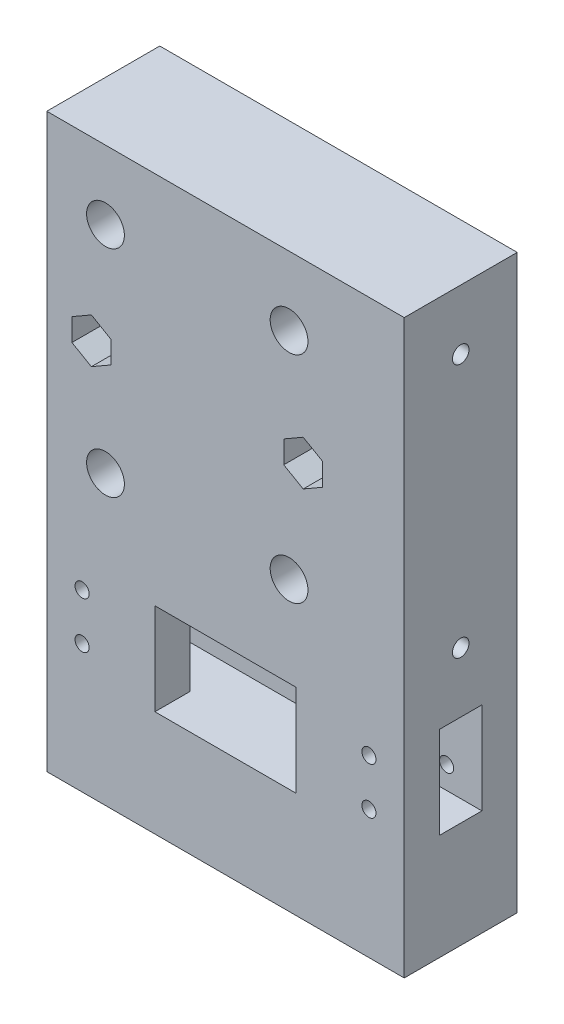
SolidWorks part; units mm, degrees
other "Markup1"
sketch "Sketch8" plane through (21.3115, 25, 0) normal (0.306, 0.1864, -0.9336) x (-0.9512, 0.0181, -0.3081)
ref_plane "Front Plane" through (0, 0, 0) normal (0, 0, 1) x (1, 0, 0)
ref_plane "Top Plane" through (0, 0, 0) normal (0, 1, 0) x (1, 0, 0)
ref_plane "Right Plane" through (0, 0, 0) normal (1, 0, 0) x (0, 0, -1)
sketch "Sketch1" plane through (0, 0, 0) normal (0, 0, 1) x (1, 0, 0)
  line L0 (0, 25) -> (0, -25) construction
  line L1 (21.3115, 25) -> (-21.3115, 25)
  line L2 (21.3115, 25) -> (21.3115, -25)
  line L3 (21.3115, -25) -> (-21.3115, -25)
  line L4 (-21.3115, 25) -> (-21.3115, -25)
  line L5 (21.3115, 25) -> (-21.3115, -25) construction
  line L6 (21.3115, -25) -> (-21.3115, 25) construction
  line L7 (-21.3115, 0) -> (21.3115, 0) construction
  circle A0 centre (-13, -15.25) radius 2.677
  circle A1 centre (13, -15.25) radius 2.677
  circle A2 centre (13, 15.25) radius 2.677
  circle A3 centre (-13, 15.25) radius 2.677
  point P0 (0, 0)
  dimension "D1" = 30.5
  dimension "D2" = 26
  dimension "D3" = 50
extrude "Boss-Extrude1" add sketch "Sketch1" along normal blind 16
sketch "Sketch2" plane through (0, 0, 0) normal (0, 0, 1) x (1, 0, 0)
  circle A0 centre (0, 0) radius 11
  dimension "D1" = 22
extrude "Cut-Extrude2" cut sketch "Sketch2" along normal blind 11
sketch "Sketch3" plane through (0, 0, 0) normal (0, 0, -1) x (-1, 0, 0)
  line L0 (0, 0) -> (-18.0234, 0) construction
  line L1 (0, 0) -> (0, 5.0894) construction
  circle A0 centre (-15, 0) radius 1.75
  circle A1 centre (15, 0) radius 1.75
  dimension "D1" = 15
  dimension "D2" = 3.5
extrude "Cut-Extrude3" cut sketch "Sketch3" against normal blind 10
sketch "Sketch9" plane through (0, 0, 0) normal (0, 0, -1) x (-1, 0, 0)
  line L0 (0, -11) -> (0, 11) construction
  line L1 (-15, 3.1754) -> (-17.75, 1.5877)
  line L2 (-17.75, 1.5877) -> (-17.75, -1.5877)
  line L3 (-17.75, -1.5877) -> (-15, -3.1754)
  line L4 (-15, -3.1754) -> (-12.25, -1.5877)
  line L5 (-12.25, -1.5877) -> (-12.25, 1.5877)
  line L6 (-12.25, 1.5877) -> (-15, 3.1754)
  line L7 (12.25, 1.5877) -> (15, 3.1754)
  line L8 (12.25, -1.5877) -> (12.25, 1.5877)
  line L9 (15, -3.1754) -> (12.25, -1.5877)
  line L10 (17.75, -1.5877) -> (15, -3.1754)
  line L11 (17.75, 1.5877) -> (17.75, -1.5877)
  line L12 (15, 3.1754) -> (17.75, 1.5877)
  circle A0 centre (-15, 0) radius 2.75 construction
  circle A1 centre (0, 0) radius 11 construction
  point P1 (-17.75, 0)
  dimension "D1" = 5.5
extrude "Cut-Extrude6" cut sketch "Sketch9" against normal through all from offset 5 offset against normal yes
sketch "Sketch10" plane through (0, 0, 0) normal (0, 0, 1) x (1, 0, 0)
  line L0 (21.3115, -25) -> (-21.3115, -25)
  line L1 (-21.3115, -25) -> (21.3115, -25) construction
  line L2 (-21.3115, -25) -> (-21.3115, -41)
  line L3 (-21.3115, -41) -> (21.3115, -41)
  line L4 (21.3115, -41) -> (21.3115, -25)
  dimension "D1" = 16
extrude "Boss-Extrude2" add sketch "Sketch10" along normal up to surface (16 mm away) up to face at (15, 0, 16)
sketch "Sketch14" plane through (-21.3115, 0, 0) normal (-1, 0, 0) x (0, 0, 1)
  line L0 (16, -41) -> (0, -41) construction
  line L1 (5, -41) -> (11, -41)
  line L2 (5, -41) -> (5, -28)
  line L3 (5, -28) -> (11, -28)
  line L4 (11, -41) -> (11, -28)
  line L7 (0, -41) -> (16, -41) construction
  point P6 (8, -41)
  point P7 (8, -41)
  dimension "D1" = 13
  dimension "D2" = 6
extrude "Cut-Extrude7" cut sketch "Sketch14" against normal through all
sketch "Sketch16" plane through (21.3115, 0, 0) normal (1, 0, 0) x (0, 0, -1)
  line L0 (-8, -28) -> (-8, 25)
  line L1 (-11, -28) -> (-5, -28) construction
  line L2 (-16, 25) -> (0, 25) construction
  line L3 (0, -41) -> (0, 25) construction
  line L4 (-16, 25) -> (0, 25)
  line L5 (-16, 25) -> (-16, -28)
  line L6 (-16, -28) -> (0, -28)
  line L7 (0, 25) -> (0, -28)
  line M6 (-11, -28) -> (-5, -28)
  line M9 (0, -41) -> (0, 25)
  line M10 (0, 25) -> (-16, 25)
  line M11 (-16, 25) -> (-16, -41)
extrude "Boss-Extrude3" add sketch "Sketch16" along normal blind 8 contours L6 L0 M11 M6 M10 | L6 L0 M6 M9 M10
sketch "Sketch17" plane through (29.3115, 0, 0) normal (1, 0, 0) x (0, 0, -1)
  line L0 (-8, -28) -> (-8, 25)
  line L1 (-16, -28) -> (0, -28) construction
  line L2 (0, 25) -> (-16, 25) construction
  line L3 (-8, -1.5) -> (0, -1.5)
  line L4 (0, -28) -> (0, 25) construction
  circle A0 centre (-8, 16.5) radius 1.175
  circle A1 centre (-8, -19.5) radius 1.175
  point P8 (-8, -1.5)
  dimension "D2" = 2.35
  dimension "D1" = 18
extrude "Cut-Extrude9" cut sketch "Sketch17" against normal blind 8 contours L0 A0 | L0 A0 | A1 L0 | A1 L0
sketch "Sketch18" plane through (0, 0, 0) normal (0, 0, -1) x (-1, 0, 0)
  line L0 (-25.3115, -28) -> (-25.3115, 25)
  line L1 (-29.3115, -28) -> (-21.3115, -28) construction
  line L2 (-29.3115, 25) -> (21.3115, 25) construction
  line L3 (-25.3115, -1.5) -> (-29.3115, -1.5)
  line L4 (-26.2115, 18.5) -> (-24.4115, 18.5)
  line L5 (-26.2115, 18.5) -> (-26.2115, 14.5)
  line L6 (-26.2115, 14.5) -> (-24.4115, 14.5)
  line L7 (-24.4115, 18.5) -> (-24.4115, 14.5)
  line L8 (-26.2115, 18.5) -> (-24.4115, 14.5) construction
  line L9 (-26.2115, 14.5) -> (-24.4115, 18.5) construction
  line L10 (-29.3115, -28) -> (-29.3115, 25) construction
  line L11 (-26.2115, -17.5) -> (-24.4115, -17.5)
  line L12 (-24.4115, -21.5) -> (-24.4115, -17.5)
  line L13 (-26.2115, -21.5) -> (-24.4115, -21.5)
  line L14 (-26.2115, -21.5) -> (-26.2115, -17.5)
  point P6 (-25.3115, 16.5)
  point P11 (-25.3115, -1.5)
  dimension "D1" = 18
  dimension "D2" = 4
  dimension "D3" = 1.8
extrude "Cut-Extrude10" cut sketch "Sketch18" against normal blind 10.2 contours L7 L4 L0 L6 | L5 L6 L0 L4 | L14 L11 L12 L13
sketch "Sketch15" plane through (0, 0, 0) normal (0, 0, -1) x (-1, 0, 0)
  line L0 (21.3115, -41) -> (-21.3115, -41) construction
  line L1 (-29.3115, -23.2996) -> (21.3115, -23.2996)
  line L2 (-21.3115, -41) -> (-21.3115, -28)
  line L3 (-29.3115, -28) -> (-29.3115, 25) construction
  line L4 (-4, -23.2996) -> (-4, -41)
  line L7 (-21.3115, -41) -> (-21.3115, -28) construction
  line L8 (-21.3115, -28) -> (-21.3115, -41) construction
  line L9 (-21.3115, -34.5) -> (21.3115, -34.5)
  line L10 (21.3115, 25) -> (21.3115, -41) construction
  line L11 (21.3115, -34.5) -> (21.3115, -28)
  line L12 (21.3115, -28) -> (0, -28)
  line L13 (0, -28) -> (0, -41)
  circle A2 centre (16.3115, -37.8) radius 1
  circle A3 centre (16.3115, -31.2) radius 1
  point P11 (-21.3115, -41)
  dimension "D1" = 5
  dimension "D2" = 3.2
extrude "Cut-Extrude8" cut sketch "Sketch15" against normal through all and the other way through all
sketch "Sketch6" plane through (0, -25, 0) normal (0, -1, 0) x (1, 0, 0)
  line L1 (4.517, 11) -> (-4.517, 11)
  line L2 (4.517, 11) -> (4.517, 13.3875)
  line L3 (4.517, 13.3875) -> (-4.517, 13.3875)
  line L4 (-4.517, 11) -> (-4.517, 13.3875)
  line L5 (4.517, 11) -> (-4.517, 13.3875) construction
  line L6 (4.517, 13.3875) -> (-4.517, 11) construction
  point P0 (0, 12.1938)
  point P5 (0, 11)
  dimension "D1" = 11
extrude "Cut-Extrude5" cut sketch "Sketch6" against normal blind 20 and the other way through all
sketch "Sketch20" plane through (0, -28, 0) normal (0, -1, 0) x (-1, 0, 0)
  line L1 (-21.3115, -16) -> (-29.3115, -16)
  line L2 (-21.3115, -16) -> (-21.3115, 0)
  line L3 (-21.3115, 0) -> (-29.3115, 0)
  line L4 (-29.3115, -16) -> (-29.3115, 0)
extrude "Boss-Extrude5" add sketch "Sketch20" along normal up to surface (13 mm away) up to face at (0, -41, 12.8469)
sketch "Sketch21" plane through (0, -41, 0) normal (0, -1, 0) x (-1, 0, 0)
  line L0 (-29.3115, -16) -> (-29.3115, 0) construction
  line L1 (-21.3115, -11) -> (-29.3115, -11)
  line L2 (-21.3115, -11) -> (-21.3115, -5)
  line L3 (-21.3115, -5) -> (-29.3115, -5)
  line L4 (-29.3115, -11) -> (-29.3115, -5)
extrude "Cut-Extrude11" cut sketch "Sketch21" against normal up to surface (13 mm away) up to face at (0, -28, 9)
sketch "Sketch22" plane through (0, 0, 0) normal (0, 0, -1) x (-1, 0, 0)
  line L0 (21.3115, -41) -> (-29.3115, -41) construction
  line L1 (-29.3115, -41) -> (-29.3115, 25) construction
  circle A0 centre (-24.3115, -37.8) radius 1
  circle A3 centre (-24.3115, -31.2) radius 1
  point P6 (0, 0)
  point P7 (0, 0)
  point P8 (0, 0)
  point P9 (0, 0)
  dimension "D1" = 2
  dimension "D2" = 3.2
  dimension "D3" = 5
  dimension "D4" = 6.6
  dimension "D5" = 2
  dimension "D6" = 5
extrude "Cut-Extrude12" cut sketch "Sketch22" against normal through all
sketch "Sketch24" plane through (0, -41, 0) normal (0, -1, 0) x (1, 0, 0)
  line L1 (-21.3115, 5) -> (29.3115, 5)
  line L2 (-21.3115, 5) -> (-21.3115, 0)
  line L3 (-21.3115, 0) -> (29.3115, 0)
  line L4 (29.3115, 5) -> (29.3115, 0)
extrude "Boss-Extrude6" add sketch "Sketch24" along normal blind 15
sketch "Sketch25" plane through (0, 0, 5) normal (0, 0, 1) x (1, 0, 0)
  line L0 (29.3115, -56) -> (-21.3115, -56) construction
  line L1 (-21.3115, -56) -> (29.3115, -56)
  line L2 (-21.3115, -56) -> (-21.3115, -41)
  line L3 (-21.3115, -41) -> (29.3115, -41)
  line L4 (29.3115, -56) -> (29.3115, -41)
extrude "Boss-Extrude7" add sketch "Sketch25" along normal up to surface (11 mm away) up to face at (23.3115, -37.8, 16)
sketch "Sketch26" plane through (0, -56, 0) normal (0, -1, 0) x (1, 0, 0)
  line L0 (4, 16) -> (4, 0)
  line L1 (29.3115, 16) -> (-21.3115, 16) construction
  line L2 (-21.3115, 0) -> (29.3115, 0) construction
  line L3 (4, 8) -> (-21.3115, 8)
  line L4 (-21.3115, 16) -> (-21.3115, 0) construction
  circle A0 centre (-14, 8) radius 1
  circle A1 centre (22, 8) radius 1
  dimension "D1" = 2
  dimension "D2" = 18
extrude "Cut-Extrude13" cut sketch "Sketch26" against normal blind 10 contours L3 A0 | L3 A0 | A1
sketch "Sketch27" plane through (0, 0, 0) normal (0, 0, -1) x (-1, 0, 0)
  line L0 (-24.4115, -21.5) -> (-24.4115, -17.5) construction
  line L1 (-24.0015, -51.1) -> (-20.0015, -51.1)
  line L2 (-24.0015, -51.1) -> (-24.0015, -52.9)
  line L3 (-24.0015, -52.9) -> (-20.0015, -52.9)
  line L4 (-20.0015, -51.1) -> (-20.0015, -52.9)
  line L5 (-24.0015, -51.1) -> (-20.0015, -52.9) construction
  line L6 (-24.0015, -52.9) -> (-20.0015, -51.1) construction
  line L8 (-26.2115, -21.5) -> (-24.4115, -21.5) construction
  line L12 (-29.3115, -56) -> (-29.3115, 25) construction
  line L13 (21.3115, -56) -> (-29.3115, -56) construction
  line L14 (-29.3115, -49.5626) -> (21.3115, -49.5626)
  line L15 (21.3115, 25) -> (21.3115, -56) construction
  line L16 (-4, -49.5626) -> (-4, -56)
  line L17 (16.0015, -52.9) -> (12.0015, -52.9)
  line L18 (12.0015, -51.1) -> (12.0015, -52.9)
  line L19 (16.0015, -51.1) -> (12.0015, -51.1)
  line L20 (16.0015, -51.1) -> (16.0015, -52.9)
  point P0 (-22.0015, -52)
  dimension "D1" = 7.31
  dimension "D2" = 3.1
extrude "Cut-Extrude14" cut sketch "Sketch27" against normal blind 10.2 contours L4 L1 L2 L3 | L20 L19 L18 L17
sketch "Sketch29" plane through (0, 0, 16) normal (0, 0, 1) x (1, 0, 0)
  line L0 (-16.3115, -31.2) -> (24.3115, -37.8)
  line L1 (24.3115, -31.2) -> (-16.3115, -37.8)
  line L2 (-16.3115, -31.2) -> (24.3115, -31.2)
  line L3 (-16.3115, -31.2) -> (-16.3115, -37.8)
  line L4 (-16.3115, -37.8) -> (24.3115, -37.8)
  line L5 (24.3115, -31.2) -> (24.3115, -37.8)
  line L7 (-6, -28) -> (14, -28)
  line L8 (-6, -28) -> (-6, -41)
  line L9 (-6, -41) -> (14, -41)
  line L10 (14, -28) -> (14, -41)
  line L11 (-6, -28) -> (14, -41) construction
  line L12 (-6, -41) -> (14, -28) construction
  point P4 (4, -34.5)
  dimension "D1" = 13
  dimension "D2" = 20
extrude "Cut-Extrude15" cut sketch "Sketch29" against normal up to surface (5 mm away) contours L10 L7 L8 L2 | L10 L2 L8 L0 L1 | L0 L8 L1 | L10 L4 L8 L9 | L10 L0 L1 L8 L4 | L10 L1 L0 up to face at (-16.3115, -32.2, 11)
